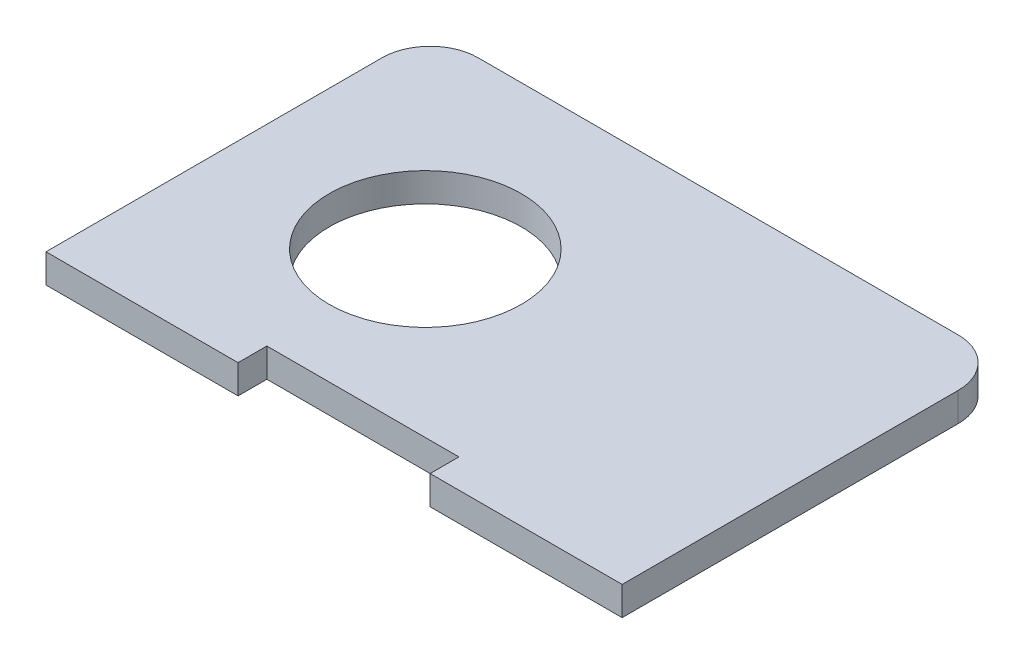
SolidWorks part; units mm, degrees
material "Acrylic (Medium-high impact)"
ref_plane "Front Plane" through (0, 0, 0) normal (0, 0, 1) x (1, 0, 0)
ref_plane "Top Plane" through (0, 0, 0) normal (0, 1, 0) x (1, 0, 0)
ref_plane "Right Plane" through (0, 0, 0) normal (1, 0, 0) x (0, 0, -1)
sketch "Sketch1" plane through (0, 0, 0) normal (0, 1, 0) x (1, 0, 0)
  line L1 (30, -20) -> (-30, -20)
  line L2 (30, -20) -> (30, 20)
  line L3 (30, 20) -> (-30, 20)
  line L4 (-30, -20) -> (-30, 20)
  line L5 (30, -20) -> (-30, 20) construction
  line L6 (30, 20) -> (-30, -20) construction
  line L7 (10, -20) -> (-10, -20)
  line L8 (10, -20) -> (10, -17)
  line L9 (10, -17) -> (-10, -17)
  line L10 (-10, -20) -> (-10, -17)
  circle A0 centre (-10.5, 0) radius 10
  point P0 (0, 0)
  dimension "D6" = 20
  dimension "D1" = 60
  dimension "D2" = 40
  dimension "D3" = 20
  dimension "D4" = 3
  dimension "D5" = 20
  dimension "D7" = 40.5
  dimension "D8" = 20
extrude "Boss-Extrude1" add sketch "Sketch1" along normal blind 3 contours L1 L10 L9 L8 L2 L3 L4 A0
fillet "Fillet1" radius 5 2 edges at (-30, 1.5, -20) (30, 1.5, -20)
